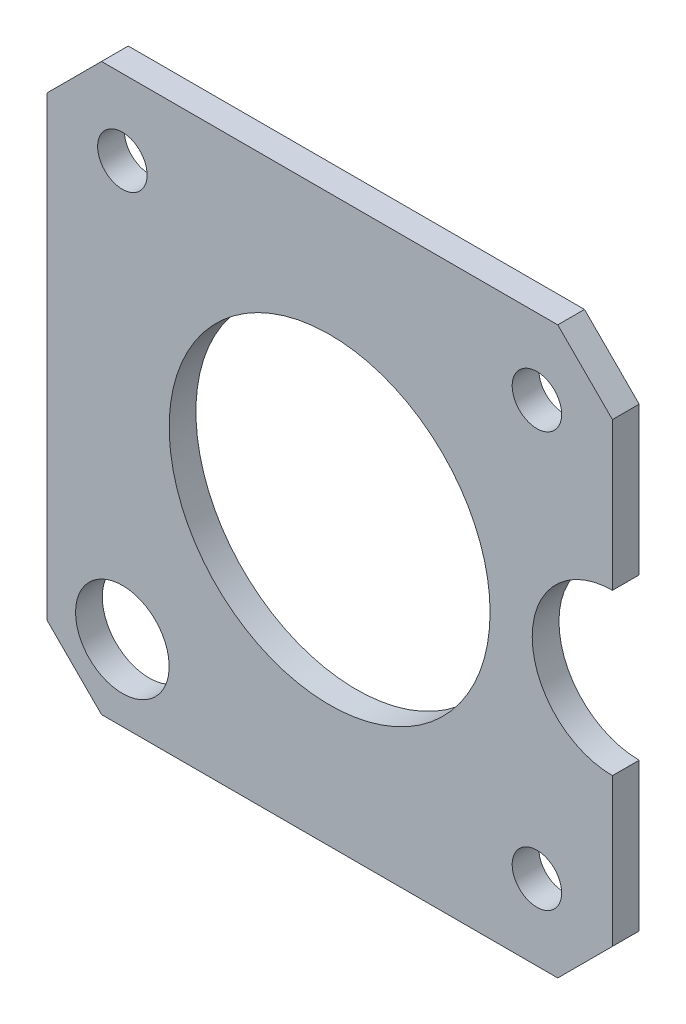
SolidWorks part; units mm, degrees
material "metacrilato"
ref_plane "Alzado" through (0, 0, 0) normal (0, 0, 1) x (1, 0, 0)
ref_plane "Planta" through (0, 0, 0) normal (0, 1, 0) x (1, 0, 0)
ref_plane "Vista lateral" through (0, 0, 0) normal (1, 0, 0) x (0, 0, -1)
sketch "Croquis1" plane through (0, 0, 0) normal (0, 0, 1) x (1, 0, 0)
  line L0 (21.15, 42.3) -> (21.15, 0) construction
  line L1 (0, 0) -> (42.3, 0)
  line L2 (0, 0) -> (0, 42.3)
  line L3 (0, 42.3) -> (42.3, 42.3)
  line L4 (42.3, 0) -> (42.3, 42.3)
  line L5 (5.65, 36.65) -> (5.65, 5.65) construction
  line L6 (5.65, 36.65) -> (5.65, 42.3) construction
  line L7 (5.65, 5.65) -> (5.65, 0) construction
  circle A0 centre (5.65, 36.65) radius 1.85
  circle A1 centre (5.65, 5.65) radius 1.85
  circle A2 centre (36.65, 5.65) radius 1.85
  circle A3 centre (36.65, 36.65) radius 1.85
  circle A4 centre (21.15, 21.15) radius 12
  dimension "D3" = 3.7
  dimension "D6" = 24
  dimension "D1" = 42.3
  dimension "D2" = 42.3
  dimension "D4" = 31
  dimension "D5" = 31
extrude "Saliente-Extruir1" add sketch "Croquis1" along normal blind 2
chamfer "Chaflán1" distance 4.09 angle 45 4 edges at (0, 42.3, 1) (0, 0, 1) (42.3, 0, 1) (42.3, 42.3, 1)
sketch "Croquis2" plane through (0, 0, 0) normal (0, 0, -1) x (-1, 0, 0)
  line L1 (-42.3, 4.09) -> (-42.3, 38.21) construction
  circle A0 centre (-42.3, 21.15) radius 6
  dimension "D1" = 12
extrude "Cortar-Extruir1" cut sketch "Croquis2" against normal through all
sketch "Croquis3" plane through (0, 0, 0) normal (0, 0, -1) x (-1, 0, 0)
  line L0 (0, 38.21) -> (0, 4.09) construction
  line L1 (-1.5, 42.3) -> (8.5, 42.3)
  line L2 (-1.5, 42.3) -> (-1.5, 0)
  line L3 (-1.5, 0) -> (8.5, 0)
  line L4 (8.5, 42.3) -> (8.5, 0)
  line L5 (-38.21, 42.3) -> (-4.09, 42.3) construction
  line L6 (-4.09, 0) -> (-38.21, 0) construction
  dimension "D1" = 1.5
  dimension "D2" = 10
extrude "Cortar-Extruir2" [suppressed] cut sketch "Croquis3" against normal through all
sketch "Croquis4" plane through (0, 0, 0) normal (0, 0, -1) x (-1, 0, 0)
  circle A0 centre (-5.65, 5.65) radius 3.5
  dimension "D1" = 7
extrude "Cortar-Extruir3" cut sketch "Croquis4" against normal through all
